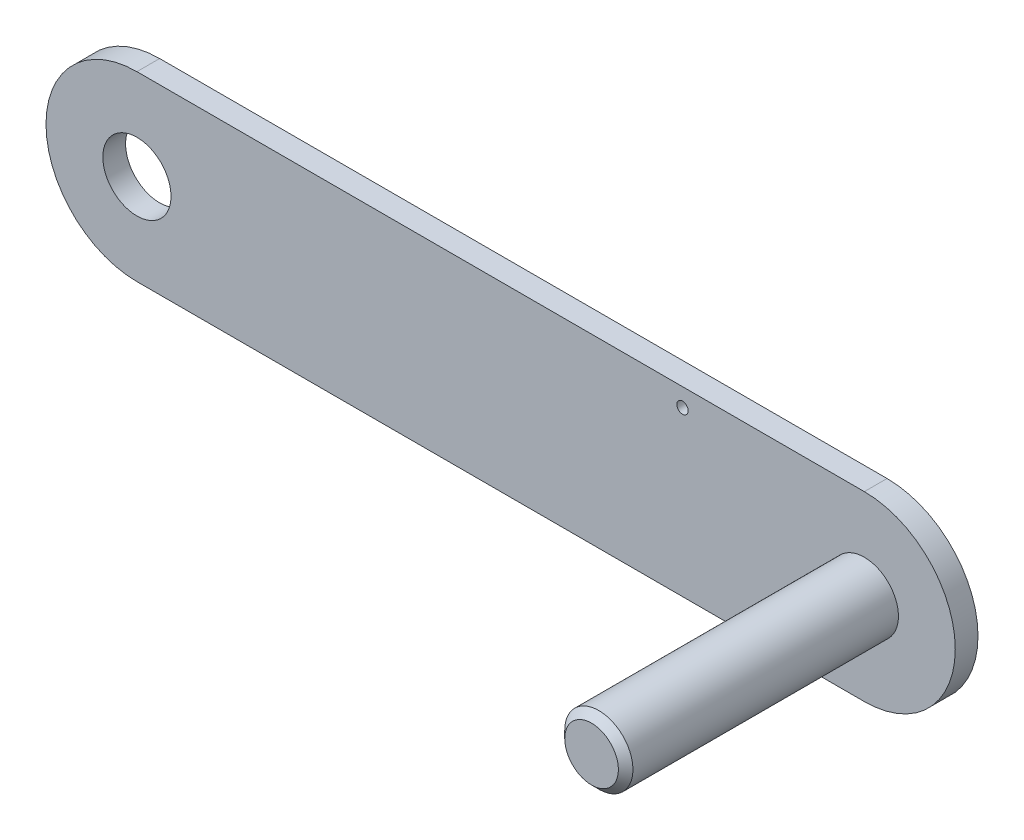
SolidWorks part; units mm, degrees
material "6061 Alloy"
ref_plane "Front Plane" through (0, 0, 0) normal (0, 0, 1) x (1, 0, 0)
ref_plane "Top Plane" through (0, 0, 0) normal (0, 1, 0) x (1, 0, 0)
ref_plane "Right Plane" through (0, 0, 0) normal (1, 0, 0) x (0, 0, -1)
sketch "Sketch1" plane through (0, 0, 0) normal (0, 0, 1) x (1, 0, 0)
  circle A0 centre (0, 0) radius 2.3813
  dimension "D1" = 4.7625
extrude "Boss-Extrude1" add sketch "Sketch1" along normal blind 19.05
chamfer "Chamfer1" distance 0.508 angle 45 1 edges at (2.3813, 0, 19.05)
sketch "Sketch3" plane through (0, 0, 0) normal (0, 0, -1) x (-1, 0, 0)
  line L1 (0, 6.35) -> (50.8, 6.35)
  line L3 (0, -6.35) -> (50.8, -6.35)
  arc A0 (0, 6.35) -> (0, -6.35) centre (0, 0) ccw
  circle A1 centre (0, 0) radius 2.3813 construction
  arc A2 (50.8, 6.35) -> (50.8, -6.35) centre (50.8, 0) cw
  circle A3 centre (50.8, 0) radius 2.3812
  dimension "D1" = 6.35
  dimension "D3" = 4.7625
  dimension "D2" = 50.8
extrude "Boss-Extrude2" add sketch "Sketch3" along normal blind 1.5875
sketch "Sketch4" plane through (0, 0, 0) normal (0, 0, 1) x (1, 0, 0)
  line L0 (-50.8, 6.35) -> (0, 6.35) construction
  circle A0 centre (-12.7, 5.08) radius 0.3969
  dimension "D1" = 0.7937
  dimension "D2" = 1.27
  dimension "D3" = 38.1
extrude "Cut-Extrude3" cut sketch "Sketch4" against normal through all
